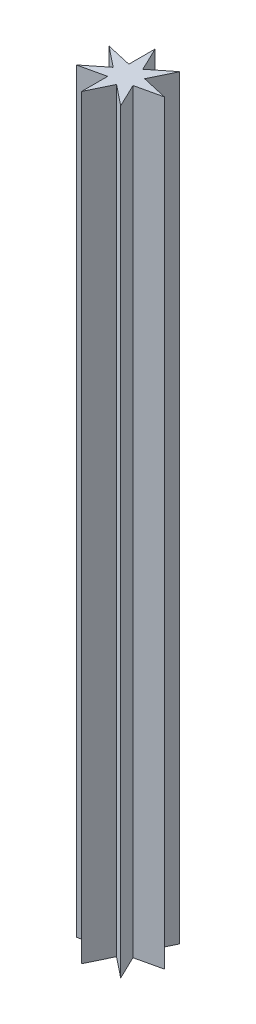
SolidWorks part; units mm, degrees
ref_plane "Front Plane" through (0, 0, 0) normal (0, 0, 1) x (1, 0, 0)
ref_plane "Top Plane" through (0, 0, 0) normal (0, 1, 0) x (1, 0, 0)
ref_plane "Right Plane" through (0, 0, 0) normal (1, 0, 0) x (0, 0, -1)
sketch "Sketch1" plane through (0, 0, 0) normal (0, 1, 0) x (1, 0, 0)
  line L0 (-1.413, 6.1908) -> (-1.413, -6.1908)
  line L1 (6.35, 0) -> (3.9592, 4.9646)
  line L2 (3.9592, 4.9646) -> (-1.413, 6.1908)
  line L3 (-1.413, 6.1908) -> (-5.7212, 2.7552)
  line L4 (-5.7212, 2.7552) -> (-5.7212, -2.7552)
  line L5 (-5.7212, -2.7552) -> (-1.413, -6.1908)
  line L6 (-1.413, -6.1908) -> (3.9592, -4.9646)
  line L7 (3.9592, -4.9646) -> (6.35, 0)
  line L8 (-1.413, 6.1908) -> (3.9592, -4.9646)
  line L9 (-5.7212, 2.7552) -> (3.9592, -4.9646)
  line L10 (3.9592, 4.9646) -> (-1.413, -6.1908)
  line L11 (6.35, 0) -> (-5.7212, 2.7552)
  line L12 (-5.7212, -2.7552) -> (3.9592, 4.9646)
  line L13 (-5.7212, -2.7552) -> (6.35, 0)
  circle A1 centre (0, 0) radius 6.35 construction
extrude "Boss-Extrude1" add sketch "Sketch1" along normal blind 127 contours L9 L12 L0 L11 | L11 L12 L8 L0 | L12 L8 L11 L10 | L9 L13 L10 L8 L11 L12 L0 | L12 L11 L8 | L0 L12 L11 | L12 L9 L0 | L10 L11 L8 | L10 L13 L8 | L13 L9 L10 | L0 L13 L9 | L12 L13 L0 L9 | L13 L0 L10 L9 | L13 L10 L9 L8 | L8 L13 L11 L10
